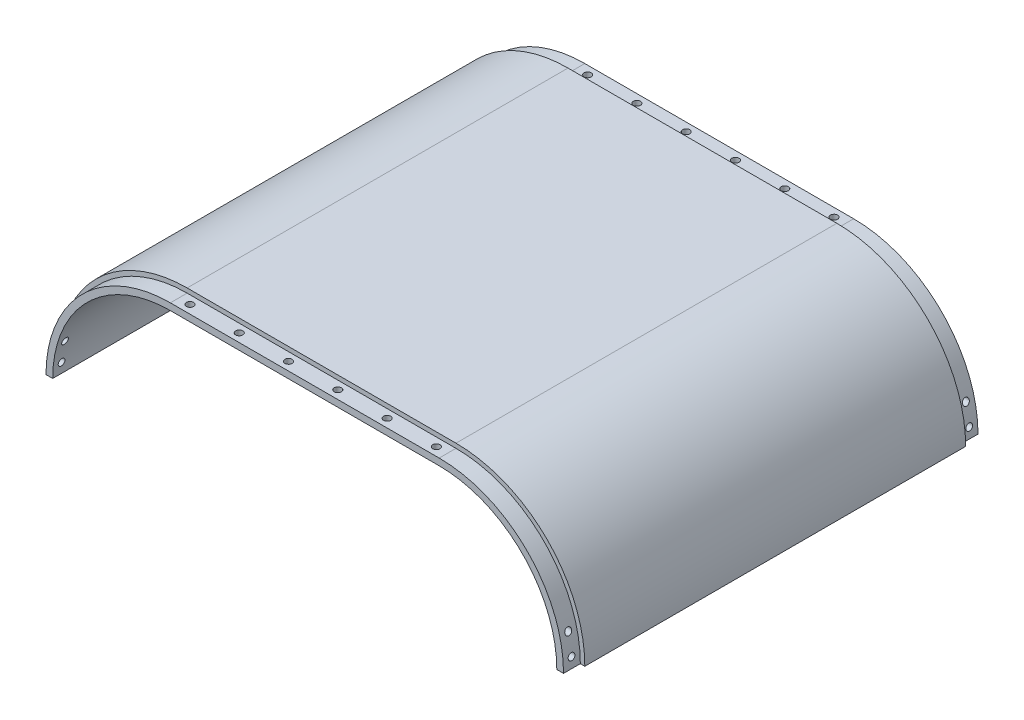
SolidWorks part; units mm, degrees
ref_plane "Front Plane" through (0, 0, 0) normal (0, 0, 1) x (1, 0, 0)
ref_plane "Top Plane" through (0, 0, 0) normal (0, 1, 0) x (1, 0, 0)
ref_plane "Right Plane" through (0, 0, 0) normal (1, 0, 0) x (0, 0, -1)
sketch "Sketch1" plane through (0, 0, 0) normal (0, 0, 1) x (1, 0, 0)
  line L2 (-60, -57.5) -> (60, -57.5) construction
  line L3 (60, 57.5) -> (-60, 57.5)
  line L4 (-60, -52.5) -> (60, -52.5) construction
  line L5 (60, 52.5) -> (-60, 52.5)
  line L10 (57.05, 52.5) -> (52.95, 52.5)
  line L11 (35.05, 52.5) -> (30.95, 52.5)
  line L12 (13.05, 52.5) -> (8.95, 52.5)
  line L13 (-8.95, 52.5) -> (-13.05, 52.5)
  line L14 (-52.95, 52.5) -> (-57.05, 52.5)
  line L15 (-30.95, 52.5) -> (-35.05, 52.5)
  line L16 (-117.5, 0) -> (-112.5, 0)
  line L17 (-133.4321, 0) -> (-117.5, 0) construction
  line L18 (-112.5, 0) -> (112.5, 0) construction
  line L19 (112.5, 0) -> (117.5, 0)
  line L20 (117.5, 0) -> (142.1657, 0) construction
  arc A2 (-60, 57.5) -> (-117.5, 0) centre (-60, 0) ccw
  arc A3 (117.5, 0) -> (60, 57.5) centre (60, 0) ccw
  arc A4 (-60, 52.5) -> (-112.5, 0) centre (-60, 0) ccw
  arc A5 (112.5, 0) -> (60, 52.5) centre (60, 0) ccw
  arc A6 (-110.1443, 15.55) -> (-111.2362, 11.45) centre (-60, 0) ccw
  arc A7 (-112.0898, 6.55) -> (-112.4428, 2.45) centre (-60, 0) ccw
  arc A10 (112.4428, 2.45) -> (112.0898, 6.55) centre (60, 0) ccw
  arc A11 (111.2362, 11.45) -> (110.1443, 15.55) centre (60, 0) ccw
  arc A12 (60, -57.5) -> (117.5, 0) centre (60, 0) ccw construction
  arc A13 (60, -57.5) -> (60, 57.5) centre (60, 0) ccw construction
  arc A14 (60, -52.5) -> (112.5, 0) centre (60, 0) ccw construction
  arc A15 (60, -52.5) -> (60, 52.5) centre (60, 0) ccw construction
  arc A16 (-112.5, 0) -> (-60, -52.5) centre (-60, 0) ccw construction
  arc A17 (-60, 52.5) -> (-60, -52.5) centre (-60, 0) ccw construction
  arc A18 (-117.5, 0) -> (-60, -57.5) centre (-60, 0) ccw construction
  arc A19 (-60, 57.5) -> (-60, -57.5) centre (-60, 0) ccw construction
  dimension "D1" = 5
extrude "Boss-Extrude1" add sketch "Sketch1" along normal mid plane 185 contours A5 L19 A3 L3 A2 L16 A4 L5 A11
sketch "Sketch2" plane through (0, 0, 0) normal (1, 0, 0) x (0, 0, -1)
  line L0 (-92.5, 57.5) -> (-92.5, 0) construction
  line L1 (-92.5, 0) -> (92.5, 0) construction
  circle A0 centre (-88.75, 4.5) radius 1.5
  circle A1 centre (-88.75, 13.5) radius 1.5
  point P8 (0, 0)
  dimension "D1" = 3
  dimension "D4" = 3
  dimension "D2" = 3.75
  dimension "D3" = 4.5
  dimension "D5" = 9
extrude "Cut-Extrude1" cut sketch "Sketch2" against normal through all both and the other way through all
sketch "Sketch4" plane through (0, 57.5, 0) normal (0, 1, 0) x (1, 0, 0)
  line L0 (0, -180.3175) -> (0, -193.1229) construction
  line L1 (60, -92.5) -> (-60, -92.5) construction
  circle A0 centre (-55, -88.75) radius 1.6
  circle A1 centre (-33, -88.75) radius 1.6
  circle A2 centre (-11, -88.75) radius 1.6
  circle A3 centre (11, -88.75) radius 1.6
  circle A4 centre (33, -88.75) radius 1.6
  circle A5 centre (55, -88.75) radius 1.6
  dimension "D1" = 3.2
  dimension "D2" = 3.75
  dimension "D4" = 11
  dimension "D3" = 6
extrude "Cut-Extrude2" cut sketch "Sketch4" against normal through all both
sketch "Sketch5" plane through (0, 0, -92.5) normal (0, 0, -1) x (-1, 0, 0)
  line L0 (117.5, 0) -> (112.5, 0) construction
  line L1 (-112.5, 0) -> (-117.5, 0) construction
  line L2 (-60, 57.5) -> (60, 57.5) construction
  line L3 (117.5, 0) -> (112.5, 0)
  line L4 (-112.5, 0) -> (-117.5, 0)
  line L5 (-60, 57.5) -> (60, 57.5)
  line L6 (-60, 55.5) -> (60, 55.5)
  arc A0 (-60, 57.5) -> (-117.5, 0) centre (-60, 0) ccw construction
  arc A1 (117.5, 0) -> (60, 57.5) centre (60, 0) ccw construction
  arc A2 (-60, 57.5) -> (-117.5, 0) centre (-60, 0) ccw
  arc A3 (117.5, 0) -> (60, 57.5) centre (60, 0) ccw
  arc A4 (115.5, 0) -> (60, 55.5) centre (60, 0) ccw
  arc A5 (-60, 55.5) -> (-115.5, 0) centre (-60, 0) ccw
  arc M6 (117.5, 0) -> (60, 57.5) centre (60, 0) ccw
  line M7 (60, 57.5) -> (-60, 57.5)
  arc M8 (-60, 57.5) -> (-117.5, 0) centre (-60, 0) ccw
  line M9 (-117.5, 0) -> (-112.5, 0)
  dimension "D1" = 2
extrude "Cut-Extrude3" cut sketch "Sketch5" against normal blind 7.5 contours A5 L6 A4 L3 M6 M7 M8 M9
mirror "Mirror1" about plane through (0, 0, 0) normal (0, 0, 1) of "Cut-Extrude3", "Cut-Extrude1", "Cut-Extrude2"
